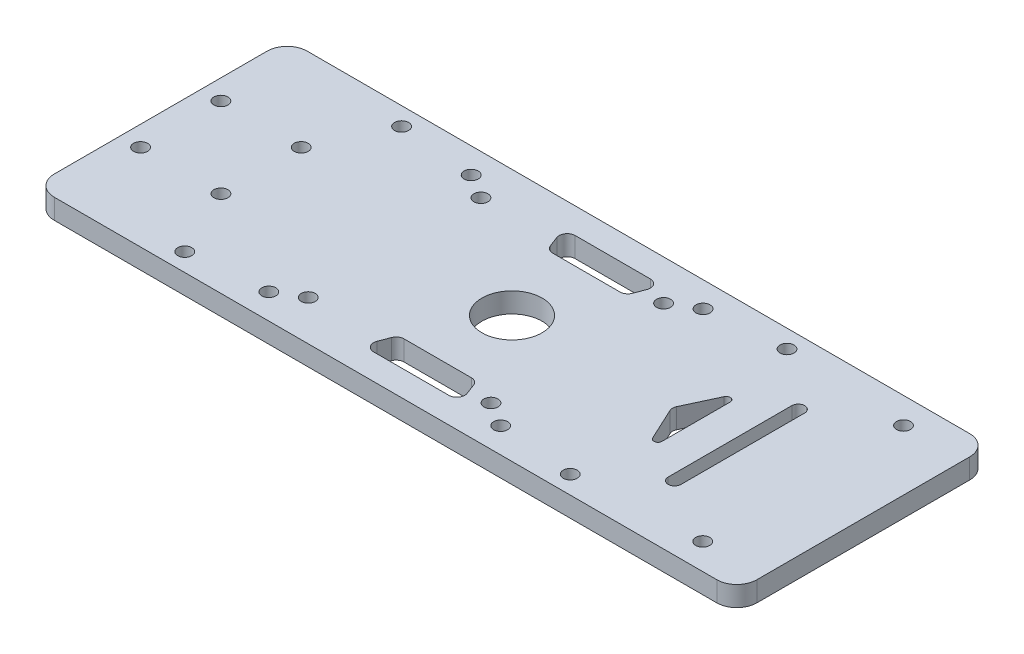
SolidWorks part; units mm, degrees
material "Thornel Mat VMA"
ref_plane "Front Plane" through (0, 0, 0) normal (0, 0, 1) x (1, 0, 0)
ref_plane "Top Plane" through (0, 0, 0) normal (0, 1, 0) x (1, 0, 0)
ref_plane "Right Plane" through (0, 0, 0) normal (1, 0, 0) x (0, 0, -1)
sketch "Sketch1" plane through (0, 0, 0) normal (0, 1, 0) x (1, 0, 0)
  line L1 (-87.5, 31.5) -> (87.5, 31.5)
  line L2 (-87.5, 31.5) -> (-87.5, -31.5)
  line L3 (-87.5, -31.5) -> (87.5, -31.5)
  line L4 (87.5, 31.5) -> (87.5, -31.5)
  line L5 (-87.5, 31.5) -> (87.5, -31.5) construction
  line L6 (-87.5, -31.5) -> (87.5, 31.5) construction
  point P0 (0, 0)
  dimension "D1" = 63
  dimension "D2" = 175
extrude "Boss-Extrude1" add sketch "Sketch1" along normal mid plane 5
sketch "Sketch2" plane through (0, 2.5, 0) normal (0, 1, 0) x (1, 0, 0)
  line L0 (-87.5, 31.5) -> (-87.5, -31.5) construction
  line L1 (87.5, 31.5) -> (-87.5, 31.5) construction
  line L2 (-87.5, 0) -> (87.5, 0) construction
  line L3 (87.5, -31.5) -> (87.5, 31.5) construction
  circle A0 centre (-82.5, 10) radius 1.75
  circle A1 centre (-62.5, 10) radius 1.75
  circle A2 centre (-54.5, 27) radius 1.75
  circle A3 centre (-35.37, 25.2) radius 1.75
  circle A4 centre (-29.24, 21.5) radius 1.75
  circle A5 centre (22.38, 25.2) radius 1.75
  circle A6 centre (16.26, 21.5) radius 1.75
  circle A7 centre (41.5, 27) radius 1.75
  circle A8 centre (41.5, -27) radius 1.75
  circle A9 centre (22.38, -25.2) radius 1.75
  circle A10 centre (16.26, -21.5) radius 1.75
  circle A11 centre (-29.24, -21.5) radius 1.75
  circle A12 centre (-35.37, -25.2) radius 1.75
  circle A13 centre (-62.5, -10) radius 1.75
  circle A14 centre (-54.5, -27) radius 1.75
  circle A15 centre (-82.5, -10) radius 1.75
  dimension "D1" = 5
  dimension "D3" = 3.5
  dimension "D4" = 20
  dimension "D5" = 4.5
  dimension "D7" = 1.8
  dimension "D9" = 3.7
  dimension "D11" = 57.75
  dimension "D12" = 45.5
  dimension "D13" = 96
  dimension "D2" = 21.5
  dimension "D6" = 33
  dimension "D8" = 19.13
  dimension "D10" = 6.13
extrude "Cut-Extrude1" cut sketch "Sketch2" against normal through all
sketch "Sketch3" plane through (0, 2.5, 0) normal (0, 1, 0) x (1, 0, 0)
  line L0 (-8.3689, 18.5) -> (8.3689, 18.5)
  line L1 (-9.3538, 25.1) -> (0, 25.1)
  line L2 (-11.2241, 22.3915) -> (-10.2392, 19.7915)
  line L5 (-10.0132, 19.1949) -> (-7.7282, 13.1625) construction
  line L6 (87.5, 31.5) -> (-87.5, 31.5) construction
  line L7 (0, 25.1) -> (0, 18.5) construction
  line L8 (11.2241, 22.3915) -> (10.2392, 19.7915)
  line L9 (9.3538, 25.1) -> (0, 25.1)
  line L10 (9.75, 18.5) -> (-9.75, 18.5) construction
  line L11 (10.1682, 19.604) -> (8.163, 14.3102) construction
  line L12 (8.3689, 18.5) -> (9.75, 18.5) construction
  line L13 (12.25, 25.1) -> (-12.25, 25.1) construction
  line L14 (9.3538, 25.1) -> (12.25, 25.1) construction
  line L15 (-87.5, 0) -> (87.5, 0) construction
  line L16 (-87.5, 31.5) -> (-87.5, -31.5) construction
  line L17 (87.5, -31.5) -> (87.5, 31.5) construction
  line L18 (45.85, 8.4893) -> (45.85, -8.4893)
  line L19 (43.9437, 8.9119) -> (40.1821, 0.8452)
  line L20 (0, -25.1) -> (0, -18.5) construction
  line L21 (9.3538, -25.1) -> (0, -25.1)
  line L22 (11.2241, -22.3915) -> (10.2392, -19.7915)
  line L23 (-11.2241, -22.3915) -> (-10.2392, -19.7915)
  line L24 (-9.3538, -25.1) -> (0, -25.1)
  line L25 (-8.3689, -18.5) -> (8.3689, -18.5)
  line L27 (43.9437, -8.9119) -> (40.1821, -0.8452)
  line L28 (43.9437, -8.9119) -> (45.85, -13) construction
  line L29 (45.85, -8.4893) -> (45.85, -13)
  line L30 (43.9437, 8.9119) -> (45.85, 13) construction
  line L31 (45.85, 8.4893) -> (45.85, 13) construction
  line L32 (55.9, 15.4) -> (55.9, -15.4) construction
  line L33 (57.5, 15.4) -> (57.5, -15.4)
  line L34 (54.3, 15.4) -> (54.3, -15.4)
  circle A0 centre (0, 0) radius 7.5
  arc A1 (-11.2241, 22.3915) -> (-9.3538, 25.1) centre (-9.3538, 23.1) cw
  arc A3 (-10.2392, 19.7915) -> (-8.3689, 18.5) centre (-8.3689, 20.5) ccw
  arc A5 (10.2392, 19.7915) -> (8.3689, 18.5) centre (8.3689, 20.5) cw
  arc A6 (11.2241, 22.3915) -> (9.3538, 25.1) centre (9.3538, 23.1) ccw
  arc A7 (11.2241, -22.3915) -> (9.3538, -25.1) centre (9.3538, -23.1) cw
  arc A8 (10.2392, -19.7915) -> (8.3689, -18.5) centre (8.3689, -20.5) ccw
  arc A9 (-10.2392, -19.7915) -> (-8.3689, -18.5) centre (-8.3689, -20.5) cw
  arc A10 (-11.2241, -22.3915) -> (-9.3538, -25.1) centre (-9.3538, -23.1) ccw
  arc A11 (45.85, 8.4893) -> (43.9437, 8.9119) centre (44.85, 8.4893) ccw
  arc A12 (40.1821, 0.8452) -> (40.1821, -0.8452) centre (41.9948, 0) ccw
  arc A13 (45.85, -8.4893) -> (43.9437, -8.9119) centre (44.85, -8.4893) cw
  arc A14 (57.5, 15.4) -> (54.3, 15.4) centre (55.9, 15.4) ccw
  arc A15 (54.3, -15.4) -> (57.5, -15.4) centre (55.9, -15.4) ccw
  point P15 (-9.75, 18.5)
  point P19 (9.75, 18.5)
  point P24 (-12.25, 25.1)
  point P31 (12.25, 25.1)
  point P55 (12.25, -25.1)
  point P56 (-12.25, -25.1)
  point P57 (9.75, -18.5)
  point P58 (-9.75, -18.5)
  point P62 (45.85, 0)
  point P65 (45.85, -13)
  point P67 (45.85, 13)
  point P71 (55.9, 0)
  dimension "D1" = 15
  dimension "D4" = 2
  dimension "D5" = 24.5
  dimension "D6" = 41.65
  dimension "D2" = 2
  dimension "D8" = 2
  dimension "D3" = 19.5
  dimension "D10" = 1
  dimension "D11" = 1
  dimension "D16" = 30
  dimension "D7" = 6.4
  dimension "D9" = 6.6
  dimension "D12" = 130
  dimension "D13" = 26
  dimension "D14" = 30.8
  dimension "D15" = 3.2
extrude "Cut-Extrude2" cut sketch "Sketch3" against normal through all contours L8 A6 L9 L1 A1 L2 A3 L0 A5 | L23 A10 L24 L21 A7 L22 A8 L25 A9
fillet "Fillet1" radius 5 4 edges at (-87.5, 0, -31.5) (87.5, 0, -31.5) (87.5, 0, 31.5) (-87.5, 0, 31.5)
sketch "Sketch4" plane through (0, 2.5, 0) normal (0, 1, 0) x (1, 0, 0)
  line L0 (87.5, -26.5) -> (87.5, 26.5) construction
  line L1 (0, 0) -> (119.16, 0) construction
  circle A0 centre (72.5, 25) radius 1.75
  circle A2 centre (72.5, -25) radius 1.75
  dimension "D1" = 3.5
  dimension "D2" = 50
  dimension "D3" = 3.5
  dimension "D4" = 15
extrude "Cut-Extrude3" cut sketch "Sketch4" against normal through all
